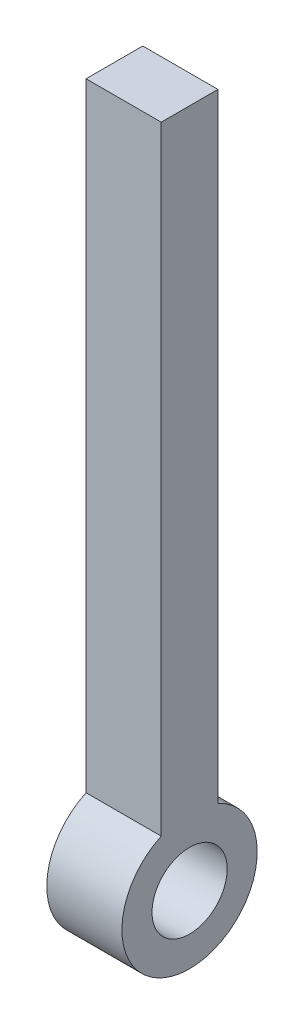
SolidWorks part; units mm, degrees
material "ABS"
ref_plane "前视基准面" through (0, 0, 0) normal (0, 0, 1) x (1, 0, 0)
ref_plane "上视基准面" through (0, 0, 0) normal (0, 1, 0) x (1, 0, 0)
ref_plane "右视基准面" through (0, 0, 0) normal (1, 0, 0) x (0, 0, -1)
other "Configuration Table"
sketch "草图1" plane through (0, 0, 0) normal (1, 0, 0) x (0, 0, -1)
  line L2 (-18.8665, 40.8541) -> (-18.8665, 452.1797)
  line L3 (-18.8665, 452.1797) -> (18.8665, 452.1797)
  line L4 (18.8665, 40.8541) -> (18.8665, 452.1797)
  line L5 (0, 25) -> (0, 0)
  circle A0 centre (0, 0) radius 25
  arc A1 (-18.8665, 40.8541) -> (18.8665, 40.8541) centre (0, 0) ccw
  point P9 (18.8665, 36.381)
  dimension "D1" = 50
  dimension "D2" = 90
extrude "凸台-拉伸1" add sketch "草图1" along normal blind 50 contours L2 A1 L4 L3 A0
